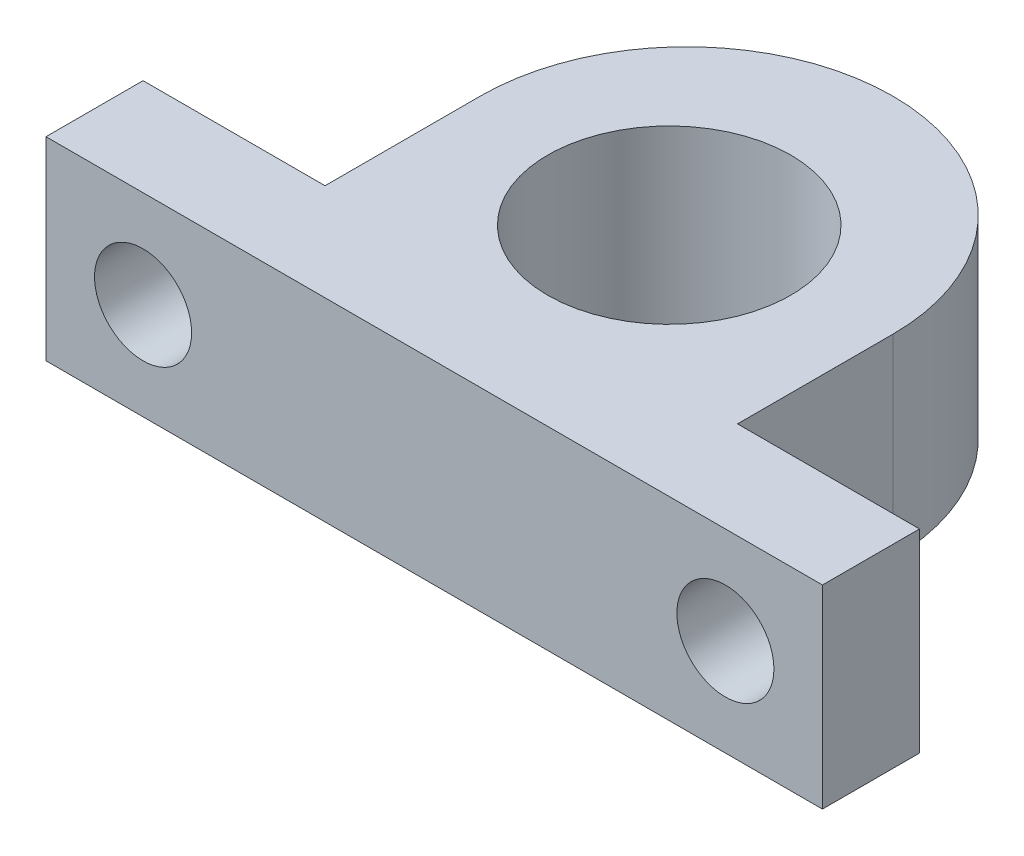
SolidWorks part; units mm, degrees
ref_plane "Front Plane" through (0, 0, 0) normal (0, 0, 1) x (1, 0, 0)
ref_plane "Top Plane" through (0, 0, 0) normal (0, 1, 0) x (1, 0, 0)
ref_plane "Right Plane" through (0, 0, 0) normal (1, 0, 0) x (0, 0, -1)
sketch "Sketch1" plane through (0, 0, 0) normal (0, 1, 0) x (1, 0, 0)
  line L0 (-25.4, 0) -> (25.4, 0)
  line L2 (0, -55) -> (0, 55) construction
  line L4 (-25.4, 0) -> (-25.4, 6.35)
  line L5 (-25.4, 6.35) -> (-13.4937, 6.35)
  line L6 (-13.4937, 6.35) -> (-13.4938, 16.51)
  line L7 (13.4937, 6.35) -> (13.4938, 16.51)
  line L8 (25.4, 6.35) -> (13.4937, 6.35)
  line L9 (25.4, 0) -> (25.4, 6.35)
  arc A0 (-13.4938, 16.51) -> (13.4938, 16.51) centre (0, 16.51) cw
  point P4 (0, 0)
  dimension "D2" = 13.4938
  dimension "D5" = 26.9875
  dimension "D1" = 50.8
  dimension "D3" = 6.35
  dimension "D4" = 10.16
extrude "Boss-Extrude1" add sketch "Sketch1" along normal blind 12.7
sketch "Sketch2" plane through (0, 12.7, 0) normal (0, 1, 0) x (1, 0, 0)
  circle A0 centre (0, 15.3754) radius 7.9502
  dimension "D1" = 15.9004
extrude "Cut-Extrude1" cut sketch "Sketch2" against normal through all contours A0
sketch "Sketch3" plane through (0, 0, 0) normal (0, 0, 1) x (1, 0, 0)
  line L0 (-25.4, 0) -> (25.4, 0) construction
  line L2 (0, -55) -> (0, 55) construction
  line L3 (-25.4, 12.7) -> (-25.4, 0) construction
  circle A0 centre (-19.05, 6.35) radius 3.175
  circle A1 centre (19.05, 6.35) radius 3.175
  dimension "D1" = 6.35
  dimension "D2" = 6.35
extrude "Cut-Extrude2" cut sketch "Sketch3" against normal through all contours A0 | A1
